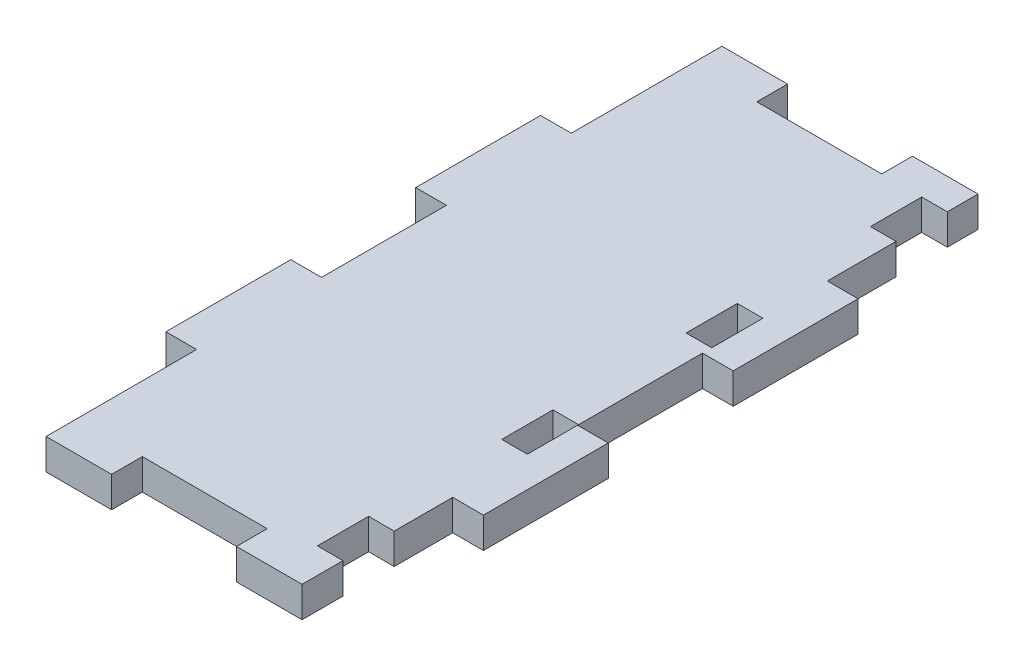
SolidWorks part; units mm, degrees
ref_plane "Front Plane" through (0, 0, 0) normal (0, 0, 1) x (1, 0, 0)
ref_plane "Top Plane" through (0, 0, 0) normal (0, 1, 0) x (1, 0, 0)
ref_plane "Right Plane" through (0, 0, 0) normal (1, 0, 0) x (0, 0, -1)
sketch "Sketch2" plane through (0, 0, 0) normal (0, 1, 0) x (1, 0, 0)
  line L0 (121, 270) -> (121, 240.585)
  line L1 (121, 240.585) -> (115, 240.585)
  line L2 (115, 240.585) -> (115, 216.195)
  line L3 (115, 216.195) -> (121, 216.195)
  line L4 (121, 216.195) -> (121, 191.805)
  line L5 (121, 191.805) -> (115, 191.805)
  line L6 (115, 191.805) -> (115, 167.415)
  line L7 (115, 167.415) -> (121, 167.415)
  line L8 (121, 167.415) -> (121, 143.025)
  line L9 (121, 143.025) -> (121, 138)
  line L10 (121, 138) -> (133.805, 138)
  line L11 (133.805, 138) -> (133.805, 144)
  line L12 (133.805, 144) -> (158.195, 144)
  line L13 (158.195, 144) -> (158.195, 138)
  line L14 (158.195, 138) -> (171, 138)
  line L15 (171, 138) -> (171, 167.415)
  line L16 (171, 167.415) -> (177, 167.415)
  line L17 (177, 167.415) -> (177, 191.805)
  line L18 (177, 191.805) -> (171, 191.805)
  line L19 (171, 191.805) -> (171, 216.195)
  line L20 (171, 216.195) -> (177, 216.195)
  line L21 (177, 216.195) -> (177, 240.585)
  line L22 (177, 240.585) -> (171, 240.585)
  line L23 (171, 240.585) -> (171, 264.975)
  line L24 (171, 264.975) -> (171, 270)
  line L25 (171, 270) -> (158.195, 270)
  line L26 (158.195, 270) -> (158.195, 264)
  line L27 (158.195, 264) -> (133.805, 264)
  line L28 (133.805, 264) -> (133.805, 270)
  line L29 (133.805, 270) -> (121, 270)
extrude "Boss-Extrude1" add sketch "Sketch2" along normal blind 6
sketch "Sketch3" plane through (0, 6, 0) normal (0, 1, 0) x (1, 0, 0)
  line L0 (171, 270) -> (158.195, 270) construction
  line L1 (166, 264) -> (171, 264)
  line L2 (166, 264) -> (166, 254)
  line L3 (166, 254) -> (171, 254)
  line L4 (171, 264) -> (171, 254)
  line L5 (171, 240.585) -> (171, 270) construction
  line L6 (166, 228) -> (166, 218)
  line L7 (166, 228) -> (171, 228)
  line L8 (171, 228) -> (171, 218)
  line L9 (166, 218) -> (171, 218)
  line L10 (166, 192) -> (166, 182)
  line L11 (166, 192) -> (171, 192)
  line L12 (171, 192) -> (171, 182)
  line L13 (166, 182) -> (171, 182)
  line L14 (166, 156) -> (166, 146)
  line L15 (166, 156) -> (171, 156)
  line L16 (171, 156) -> (171, 146)
  line L17 (166, 146) -> (171, 146)
  dimension "D1" = 6
  dimension "D2" = 10
  dimension "D3" = 5
  dimension "D4" = 0
  dimension "D5" = 4
extrude "Cut-Extrude2" cut sketch "Sketch3" against normal blind 10
